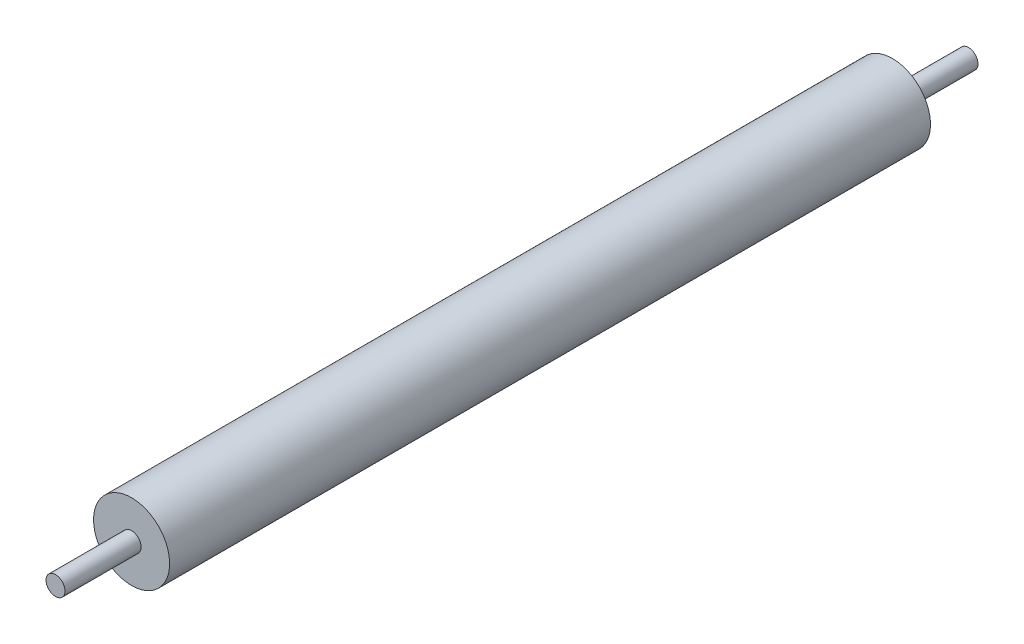
SolidWorks part; units mm, degrees
material "Plain Carbon Steel"
ref_plane "Front Plane" through (0, 0, 0) normal (0, 0, 1) x (1, 0, 0)
ref_plane "Top Plane" through (0, 0, 0) normal (0, 1, 0) x (1, 0, 0)
ref_plane "Right Plane" through (0, 0, 0) normal (1, 0, 0) x (0, 0, -1)
sketch "Sketch1" plane through (0, 0, 0) normal (0, 1, 0) x (1, 0, 0)
  line L0 (0, 120) -> (0, -120) construction
  line L1 (0, -120) -> (-2.5, -120)
  line L2 (-2.5, -120) -> (-2.5, -100)
  line L3 (-2.5, -100) -> (-10, -100)
  line L4 (-10, -100) -> (-10, 100)
  line L5 (-10, 100) -> (-2.5, 100)
  line L6 (-2.5, 100) -> (-2.5, 120)
  line L7 (-2.5, 120) -> (0, 120)
  line L8 (0, 120) -> (0, -120)
  dimension "D1" = 5
  dimension "D2" = 20
  dimension "D3" = 20
  dimension "D4" = 200
  dimension "D5" = 20
revolve "Revolve1" add sketch "Sketch1" angle 360 about L0
